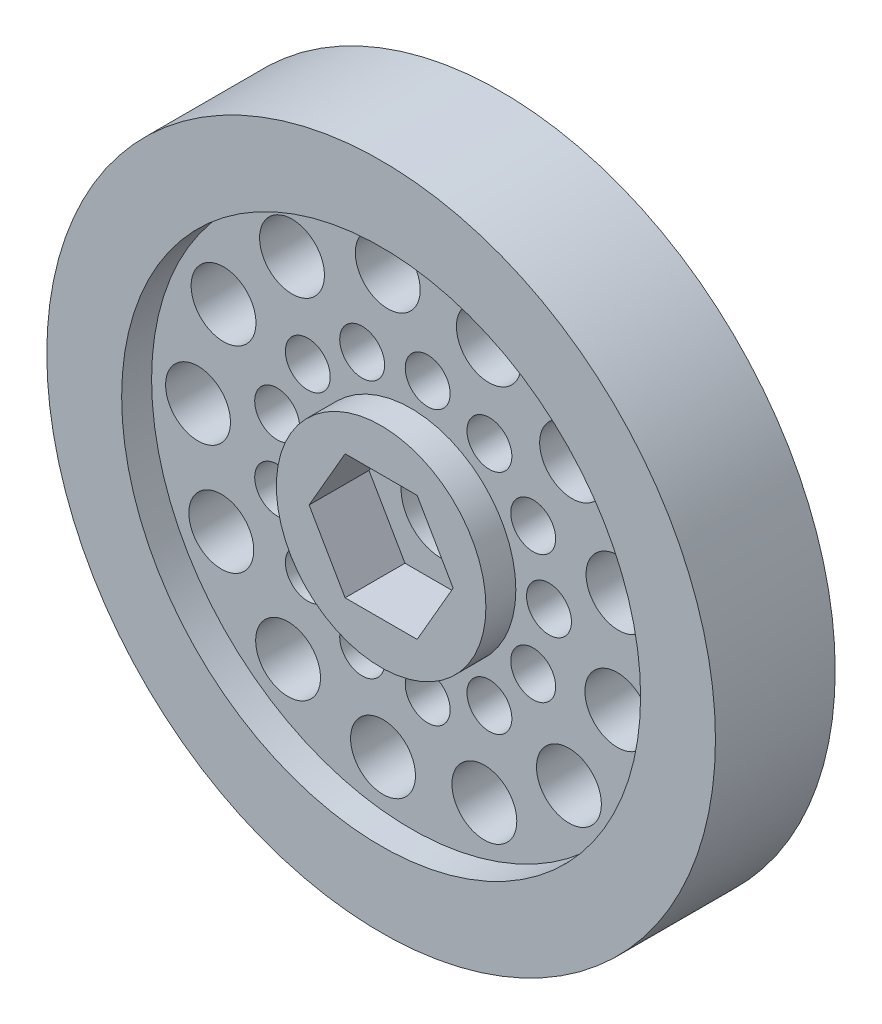
SolidWorks part; units mm, degrees
ref_plane "Front Plane" through (0, 0, 0) normal (0, 0, 1) x (1, 0, 0)
ref_plane "Top Plane" through (0, 0, 0) normal (0, 1, 0) x (1, 0, 0)
ref_plane "Right Plane" through (0, 0, 0) normal (1, 0, 0) x (0, 0, -1)
sketch "Sketch1" plane through (0, 0, 0) normal (0, 0, 1) x (1, 0, 0)
  circle A0 centre (0, 0) radius 4
  circle A1 centre (0, 0) radius 33.5
  dimension "D1" = 67
  dimension "D2" = 8
extrude "Boss-Extrude1" add sketch "Sketch1" along normal blind 12
sketch "Sketch2" plane through (0, 0, 12) normal (0, 0, 1) x (1, 0, 0)
  line L1 (7.2169, 0) -> (3.6084, 6.25)
  line L2 (3.6084, 6.25) -> (-3.6084, 6.25)
  line L3 (-3.6084, 6.25) -> (-7.2169, 0)
  line L4 (-7.2169, 0) -> (-3.6084, -6.25)
  line L5 (-3.6084, -6.25) -> (3.6084, -6.25)
  line L6 (3.6084, -6.25) -> (7.2169, 0)
  circle A0 centre (0, 0) radius 6.25 construction
  dimension "D1" = 12.5
extrude "Cut-Extrude1" cut sketch "Sketch2" against normal blind 6
sketch "Sketch3" plane through (0, 0, 12) normal (0, 0, 1) x (1, 0, 0)
  circle A0 centre (0, 0) radius 33.5 construction
  circle A1 centre (0, 0) radius 33.5 construction
  circle A2 centre (0, 0) radius 26
  circle A3 centre (0, 0) radius 10.5
  dimension "D1" = 7.5
  dimension "D2" = 23
extrude "Cut-Extrude2" cut sketch "Sketch3" against normal blind 3
sketch "Sketch4" plane through (0, 0, 0) normal (0, 0, -1) x (-1, 0, 0)
  circle A0 centre (0, 0) radius 10.5 construction
  circle A1 centre (0, 0) radius 26 construction
  circle A2 centre (0, 0) radius 10.5
  circle A3 centre (0, 0) radius 26
extrude "Cut-Extrude3" cut sketch "Sketch4" against normal blind 3
sketch "Sketch5" plane through (0, 0, 9) normal (0, 0, 1) x (1, 0, 0)
  line L0 (0, 0) -> (33.5, 0) construction
  line L1 (13.8207, 0) -> (20.7835, 4.8754) construction
  circle A0 centre (0, 0) radius 33.5 construction
  circle A1 centre (13.8207, 0) radius 2.25
  circle A2 centre (20.7835, 4.8754) radius 3.25
  dimension "D1" = 35
  dimension "D3" = 4.5
  dimension "D4" = 6.5
  dimension "D2" = 8.5
extrude "Cut-Extrude4" cut sketch "Sketch5" against normal blind 10
pattern_circular "CirPattern1" count 13 over 360 about axis through (0, 0, 0) along (0, 0, 1) of "Cut-Extrude4"
